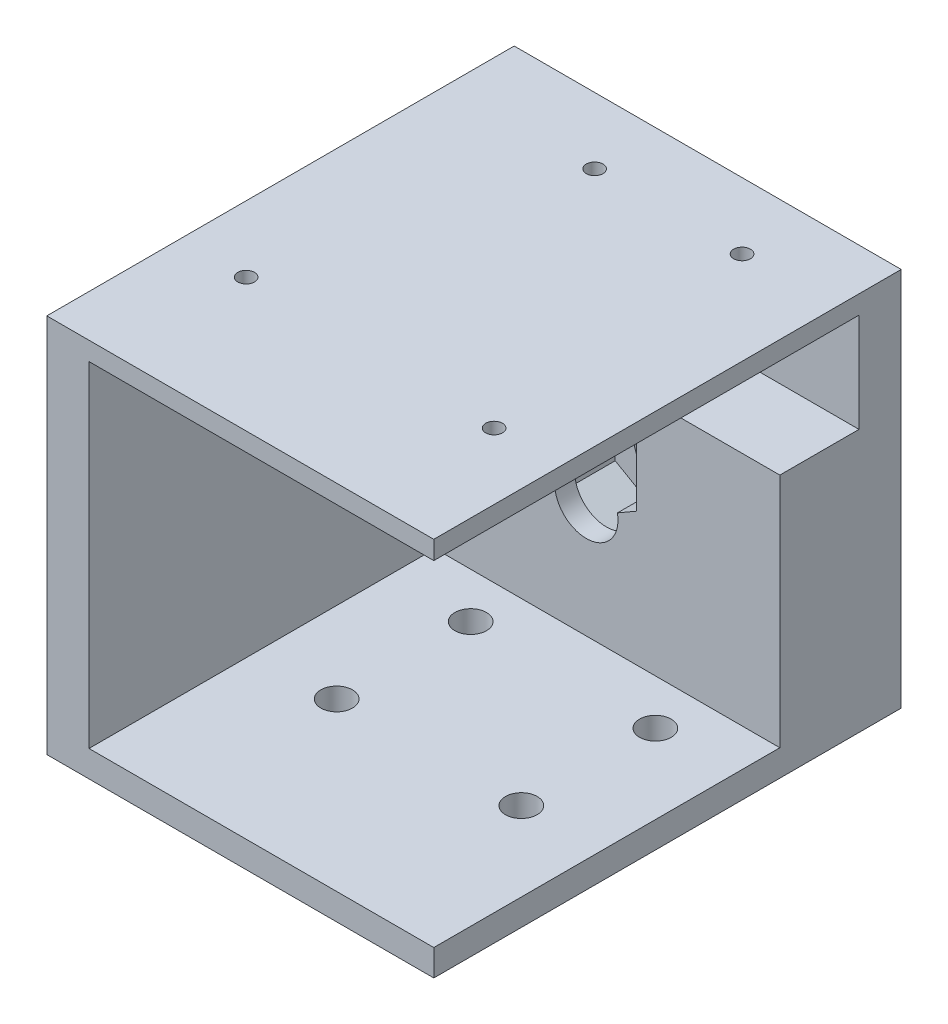
SolidWorks part; units mm, degrees
material "ABS"
ref_plane "Front Plane" through (0, 0, 0) normal (0, 0, 1) x (1, 0, 0)
ref_plane "Top Plane" through (0, 0, 0) normal (0, 1, 0) x (1, 0, 0)
ref_plane "Right Plane" through (0, 0, 0) normal (1, 0, 0) x (0, 0, -1)
sketch "Sketch2" plane through (0, 0, 0) normal (0, 1, 0) x (1, 0, 0)
  line L1 (10, -10) -> (-63.34, -10)
  line L2 (10, -10) -> (10, 78.58)
  line L3 (10, 78.58) -> (-63.34, 78.58)
  line L4 (-63.34, -10) -> (-63.34, 78.58)
  dimension "D1" = 10
  dimension "D2" = 10
  dimension "D3" = 88.58
  dimension "D4" = 73.34
extrude "Boss-Extrude1" add sketch "Sketch2" against normal blind 3.5
sketch "Sketch1" plane through (0, 0, 0) normal (0, 1, 0) x (1, 0, 0)
  line L0 (-1.925, 0) -> (1.925, 0) construction
  circle A0 centre (-7.62, 66.04) radius 1.5875
  circle A1 centre (-35.56, 66.04) radius 1.5875
  circle A2 centre (-2.54, 13.97) radius 1.5875
  circle A3 centre (-50.8, 15.24) radius 1.5875
  point P0 (0, 0)
  dimension "D8" = 3.175
  dimension "D2" = 27.94
  dimension "D3" = 66.04
  dimension "D4" = 50.8
  dimension "D5" = 2.54
  dimension "D6" = 15.24
  dimension "D7" = 7.62
  dimension "D12" = 13.97
extrude "Cut-Extrude1" cut sketch "Sketch1" against normal blind 3.5
sketch "Sketch3" plane through (0, -3.5, 0) normal (0, -1, 0) x (1, 0, 0)
  line L0 (10, -78.58) -> (-63.34, -78.58)
  line L1 (-63.34, -78.58) -> (-63.34, 10)
  line L2 (-63.34, 10) -> (-55.34, 10)
  line L3 (-63.34, 10) -> (10, 10) construction
  line L4 (-55.34, 10) -> (-55.34, -70.58)
  line L5 (-55.34, -70.58) -> (10, -70.58)
  line L6 (10, 10) -> (10, -78.58) construction
  line L7 (10, -70.58) -> (10, -78.58)
  dimension "D1" = 8
  dimension "D2" = 8
extrude "Boss-Extrude2" add sketch "Sketch3" along normal blind 63.5
sketch "Sketch4" plane through (0, -67, 0) normal (0, -1, 0) x (1, 0, 0)
  line L0 (-55.34, 10) -> (-63.34, 10) construction
  line L1 (-63.34, -78.58) -> (10, -78.58)
  line L2 (-63.34, -78.58) -> (-63.34, 10)
  line L3 (-63.34, 10) -> (10, 10)
  line L4 (10, -78.58) -> (10, 10)
  line L5 (10, -78.58) -> (10, -70.58) construction
extrude "Boss-Extrude3" add sketch "Sketch4" along normal blind 5
sketch "Sketch5" plane through (0, -72, 0) normal (0, -1, 0) x (1, 0, 0)
  line L0 (10, -78.58) -> (10, 10) construction
  circle A0 centre (-5, -21.59) radius 3
  circle A1 centre (-5, -46.99) radius 3
  circle A2 centre (-40, -21.59) radius 3
  circle A3 centre (-40, -46.99) radius 3
  point P10 (10, -34.29)
  point P11 (0, 0)
  point P12 (0, 0)
  point P13 (0, 0)
  point P14 (0, 0)
  point P15 (0, 0)
  dimension "D3" = 6
  dimension "D4" = 35
  dimension "D1" = 12.7
  dimension "D2" = 12.7
  dimension "D5" = 15
extrude "Cut-Extrude2" cut sketch "Sketch5" against normal blind 5
sketch "Sketch6" plane through (0, 0, -70.58) normal (0, 0, 1) x (1, 0, 0)
  line L0 (-55.34, -67) -> (-55.34, -3.5) construction
  line L1 (10, -67) -> (-55.34, -67)
  line L2 (10, -67) -> (10, -22.25)
  line L3 (10, -22.25) -> (-55.34, -22.25)
  line L4 (-55.34, -67) -> (-55.34, -22.25)
  point P7 (-55.34, -35.25)
  dimension "D1" = 13
extrude "Boss-Extrude4" add sketch "Sketch6" along normal blind 15
ref_plane "Plane1" through (0, 0, -70.58) normal (0, 0, 1) x (1, 0, 0)
sketch "Sketch9" plane through (0, 0, -70.58) normal (0, 0, 1) x (1, 0, 0)
  line L0 (10, -72) -> (-63.34, -72) construction
  line L1 (-17.145, -41.7478) -> (-17.145, -30.7493)
  line L2 (-17.145, -30.7493) -> (-26.67, -25.25)
  line L3 (-26.67, -25.25) -> (-36.195, -30.7493)
  line L4 (-36.195, -30.7493) -> (-36.195, -41.7478)
  line L5 (-36.195, -41.7478) -> (-26.67, -47.247)
  line L6 (-26.67, -47.247) -> (-17.145, -41.7478)
  line L7 (10, -22.25) -> (10, -3.5) construction
  line L8 (10, -22.25) -> (-55.34, -22.25) construction
  circle A0 centre (-26.67, -36.2485) radius 9.525 construction
  point P10 (-26.67, -72)
  point P13 (-26.67, -30.2733)
  dimension "D1" = 19.05
  dimension "D2" = 3
extrude "Cut-Extrude3" cut sketch "Sketch9" along normal through all
sketch "Sketch11" plane through (0, 0, -78.58) normal (0, 0, -1) x (-1, 0, 0)
  line L0 (63.34, -72) -> (-10, -72) construction
  line L2 (63.34, -72) -> (63.34, 0) construction
  circle A0 centre (26.67, -45) radius 6
  point P4 (0, 0)
  point P5 (26.67, -72)
  point P6 (26.67, -46.7697)
  point P9 (26.67, -44.511)
  point P10 (63.34, -36)
  point P11 (0, 0)
  dimension "D1" = 12
  dimension "D2" = 9
extrude "Cut-Extrude4" cut sketch "Sketch11" against normal through all
sketch "Sketch12" plane through (0, 0, -70.58) normal (0, 0, 1) x (1, 0, 0)
  line L0 (-17.145, -41.7478) -> (-17.145, -30.7493) construction
  line L1 (-17.145, -39.5007) -> (-26.67, -34.0015)
  line L2 (-26.67, -34.0015) -> (-36.195, -39.5007)
  line L3 (-36.195, -39.5007) -> (-36.195, -50.4993)
  line L4 (-36.195, -50.4993) -> (-26.67, -55.9985)
  line L5 (-26.67, -55.9985) -> (-17.145, -50.4993)
  line L6 (-17.145, -50.4993) -> (-17.145, -39.5007)
  line L7 (-36.195, -41.7478) -> (-36.195, -30.7493) construction
  circle A0 centre (-26.67, -45) radius 9.525 construction
  point P12 (0, 0)
  point P13 (-26.67, -45.1329)
extrude "Cut-Extrude5" cut sketch "Sketch12" along normal blind 11.2
